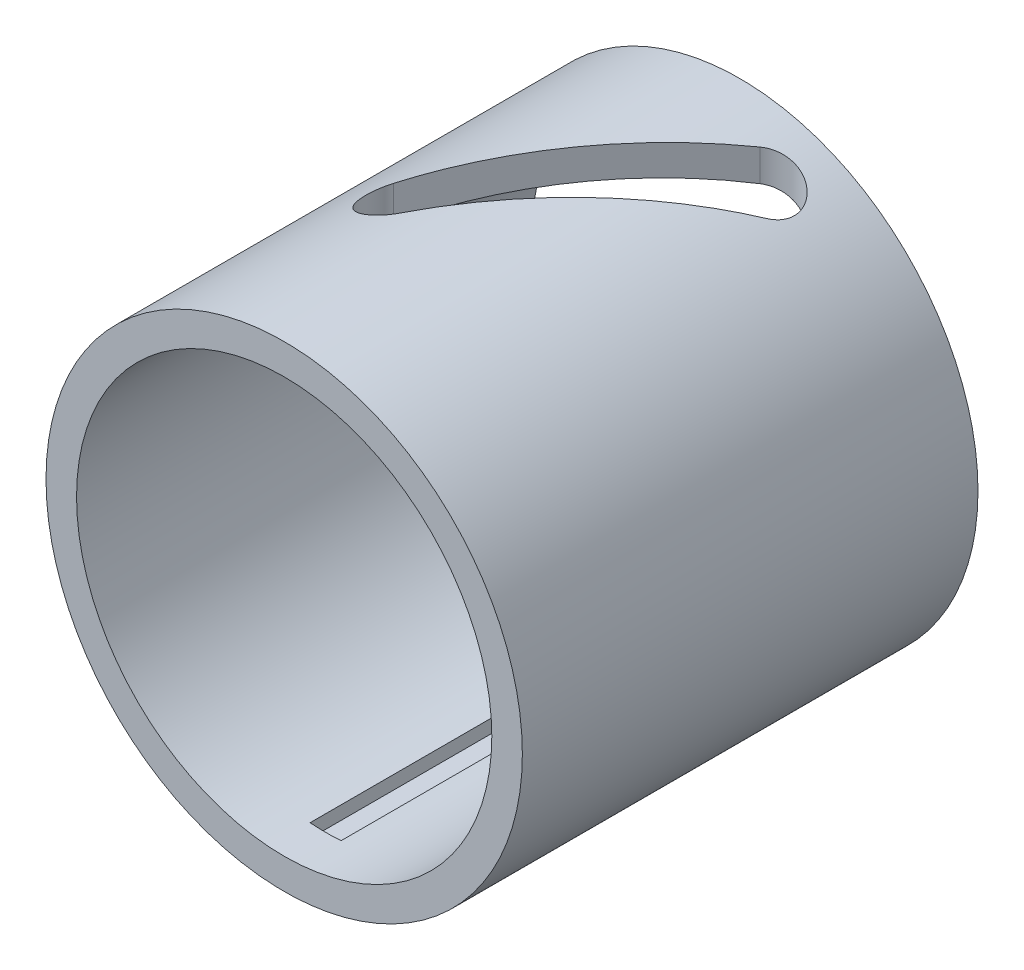
SolidWorks part; units mm, degrees
ref_plane "정면" through (0, 0, 0) normal (0, 0, 1) x (1, 0, 0)
ref_plane "윗면" through (0, 0, 0) normal (0, 1, 0) x (1, 0, 0)
ref_plane "우측면" through (0, 0, 0) normal (1, 0, 0) x (0, 0, -1)
sketch "스케치1" plane through (0, 0, 0) normal (0, 0, 1) x (1, 0, 0)
  circle A0 centre (0, 0) radius 23
  circle A1 centre (0, 0) radius 20.05
  dimension "D1" = 46
  dimension "D2" = 40.1
extrude "보스-돌출1" add sketch "스케치1" along normal blind 44
sketch "스케치2" plane through (0, 0, 0) normal (0, 1, 0) x (1, 0, 0)
  line L0 (-8.2006, -24.9315) -> (8.2006, -5.9431) construction
  line L1 (-10.471, -22.9705) -> (5.9303, -3.9821)
  line L2 (-5.9303, -26.8925) -> (10.471, -7.9041)
  line L3 (0, 0) -> (0, -15.4373) construction
  arc A0 (-10.471, -22.9705) -> (-5.9303, -26.8925) centre (-8.2006, -24.9315) ccw
  arc A1 (10.471, -7.9041) -> (5.9303, -3.9821) centre (8.2006, -5.9431) ccw
  point P2 (0, -15.4373)
  dimension "D1" = 3
extrude "컷-돌출1" cut sketch "스케치2" along normal blind 40
sketch "스케치3" plane through (0, 0, 0) normal (0, 0, 1) x (1, 0, 0)
  line L0 (0, 0) -> (0, -20.05) construction
  line L1 (-1.5, -21.3) -> (1.5, -21.3)
  line L2 (-1.5, -21.3) -> (-1.5, -18.8)
  line L3 (-1.5, -18.8) -> (1.5, -18.8)
  line L4 (1.5, -21.3) -> (1.5, -18.8)
  line L5 (-1.5, -21.3) -> (1.5, -18.8) construction
  line L6 (-1.5, -18.8) -> (1.5, -21.3) construction
  circle A0 centre (0, 0) radius 20.05 construction
  point P0 (0, -20.05)
  dimension "D1" = 3
  dimension "D2" = 2.5
extrude "컷-돌출2" cut sketch "스케치3" along normal blind 40
